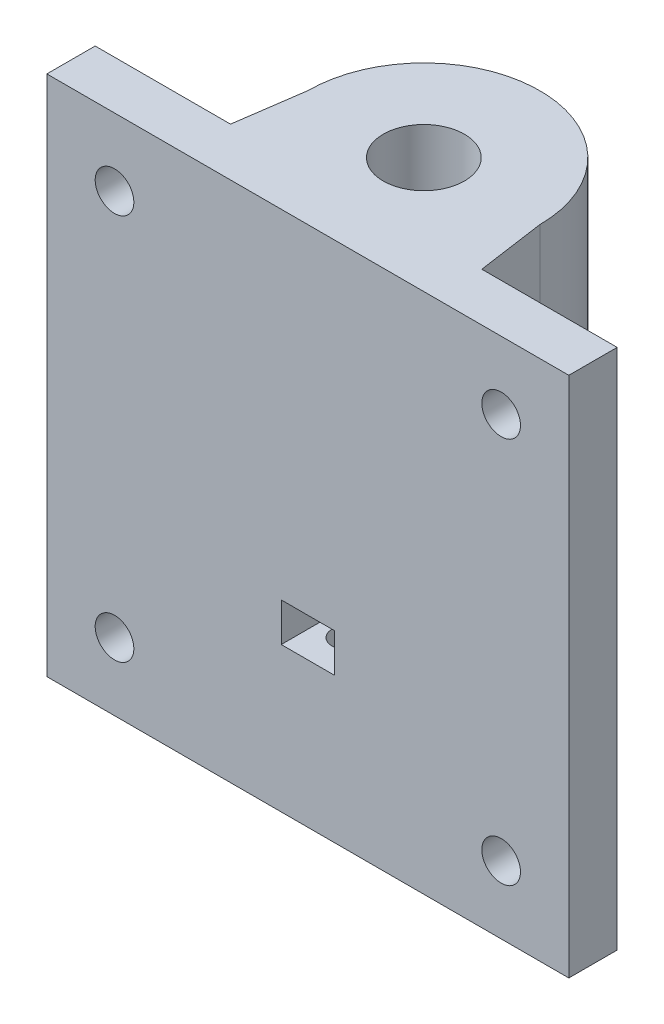
SolidWorks part; units mm, degrees
ref_plane "Płaszczyzna przednia" through (0, 0, 0) normal (0, 0, 1) x (1, 0, 0)
ref_plane "Płaszczyzna górna" through (0, 0, 0) normal (0, 1, 0) x (1, 0, 0)
ref_plane "Płaszczyzna prawa" through (0, 0, 0) normal (1, 0, 0) x (0, 0, -1)
sketch "Szkic1" plane through (0, 0, 0) normal (0, 1, 0) x (1, 0, 0)
  circle A0 centre (0, 12) radius 4.2
  circle A1 centre (0, 12) radius 12
extrude "Dodanie-wyciągnięcie1" add sketch "Szkic1" along normal blind 54
sketch "Szkic3" plane through (0, 0, 0) normal (0, 1, 0) x (1, 0, 0)
  line L0 (0, 0) -> (27, 0)
  line L1 (27, 0) -> (27, 5)
  line L2 (27, 5) -> (13, 5)
  line L3 (13, 5) -> (12, 12)
  line L4 (12, 12) -> (0, 5.1665)
  line L5 (0, 5.1665) -> (-12, 12)
  line L6 (-12, 12) -> (-13, 5)
  line L7 (-13, 5) -> (-27, 5)
  line L8 (-27, 5) -> (-27, 0)
  line L9 (-27, 0) -> (0, 0)
  circle A0 centre (0, 12) radius 12 construction
  point P3 (0, 0)
  point P14 (0, 0)
  point P15 (0, 0)
  point P16 (0, 0)
  point P17 (0, 0)
  point P18 (0, 0)
  point P19 (0, 0)
extrude "Dodanie-wyciągnięcie2" add sketch "Szkic3" along normal blind 54
sketch "Szkic4" plane through (0, 0, 0) normal (0, -1, 0) x (-1, 0, 0)
  circle A0 centre (0, 20) radius 1.5
extrude "Wytnij-wyciągnięcie1" cut sketch "Szkic4" against normal blind 20
pattern_circular "Szyk kołowy1" count 4 every 90 about axis through (0, 0, -12) along (0, 1, 0) of "Wytnij-wyciągnięcie1"
sketch "Szkic5" plane through (0, 0, 0) normal (0, 0, 1) x (1, 0, 0)
  line L1 (-2.75, 15) -> (2.75, 15)
  line L2 (-2.75, 15) -> (-2.75, 19)
  line L3 (-2.75, 19) -> (2.75, 19)
  line L4 (2.75, 15) -> (2.75, 19)
  point P4 (0, 0)
  point P5 (0, 0)
  point P6 (0, 0)
extrude "Wytnij-wyciągnięcie2" cut sketch "Szkic5" against normal blind 7 and the other way blind 3
pattern_circular "Szyk kołowy2" count 4 every 90 about axis through (0, 0, -12) along (0, 1, 0) of "Wytnij-wyciągnięcie2"
chamfer "Sfazowanie1" distance 1 angle 40 1 edges at (0, 0, -7.8)
sketch "Szkic6" plane through (0, 0, 0) normal (0, 0, 1) x (1, 0, 0)
  circle A0 centre (-20, 47) radius 2
  circle A1 centre (20, 47) radius 2
  circle A2 centre (20, 7) radius 2
  circle A3 centre (-20, 7) radius 2
extrude "Wytnij-wyciągnięcie3" cut sketch "Szkic6" against normal up to next
